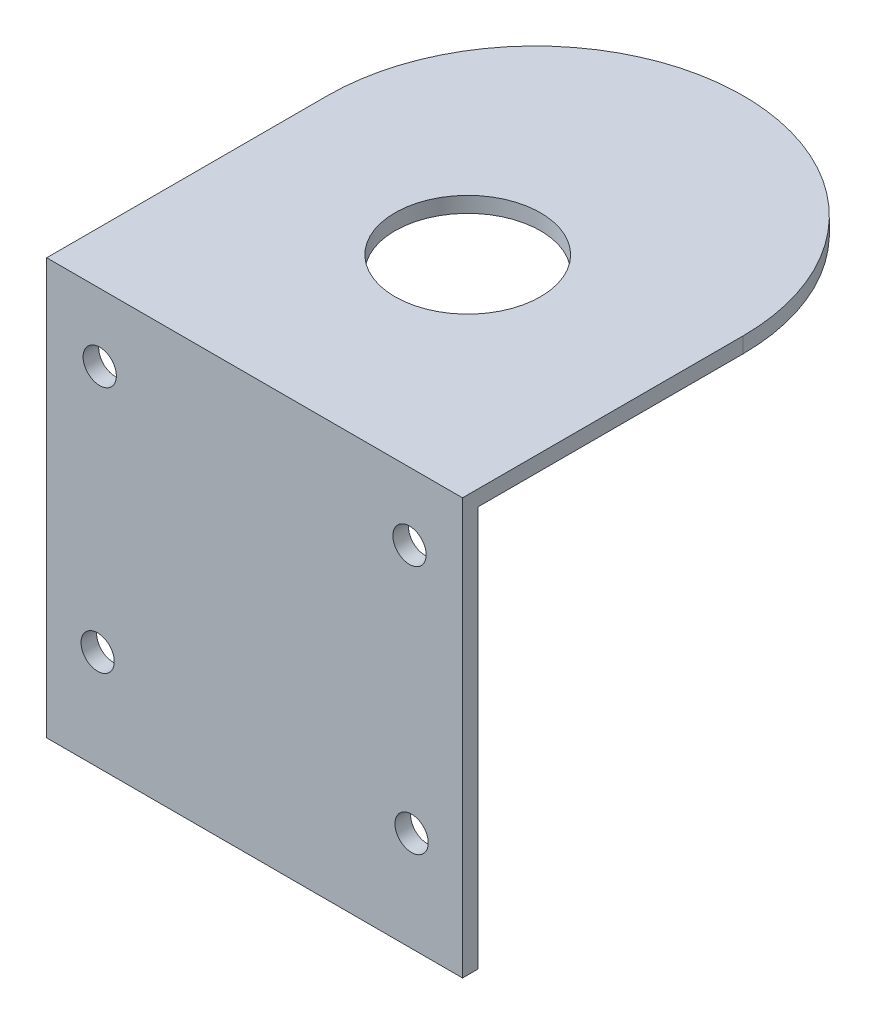
SolidWorks part; units mm, degrees
ref_plane "Front Plane" through (0, 0, 0) normal (0, 0, 1) x (1, 0, 0)
ref_plane "Top Plane" through (0, 0, 0) normal (0, 1, 0) x (1, 0, 0)
ref_plane "Right Plane" through (0, 0, 0) normal (1, 0, 0) x (0, 0, -1)
sketch "Sketch1" plane through (0, 0, 0) normal (0, 0, 1) x (1, 0, 0)
  line L0 (0, 0) -> (0, 9.1381) construction
  line L1 (-20, -20) -> (20, -20)
  line L2 (-20, -20) -> (-20, 20)
  line L3 (-20, 20) -> (20, 20)
  line L4 (20, -20) -> (20, 20)
  line L5 (-20, -20) -> (20, 20) construction
  line L6 (-20, 20) -> (20, -20) construction
  line L7 (0, 0) -> (8.2349, 0) construction
  circle A0 centre (14.9, 13.5) radius 1.6
  circle A1 centre (-14.9, 13.5) radius 1.6
  circle A4 centre (15.1, -10.3992) radius 1.6
  circle A5 centre (-15.1, -10.3992) radius 1.6
  point P0 (0, 0)
  dimension "D3" = 3.2
  dimension "D6" = 23.9
  dimension "D7" = 3.2
  dimension "D1" = 40
  dimension "D2" = 40
  dimension "D4" = 29.8
  dimension "D5" = 6.5
  dimension "D8" = 4.9
extrude "Boss-Extrude1" add sketch "Sketch1" along normal blind 1.5
sketch "Sketch3" plane through (0, 0, 0) normal (0, 0, -1) x (-1, 0, 0)
  line L0 (-20, -20) -> (-20, 20) construction
  line L1 (20, 20) -> (-20, 20)
  line L2 (20, 20) -> (20, 18.5)
  line L3 (20, 18.5) -> (-20, 18.5)
  line L4 (-20, 20) -> (-20, 18.5)
  dimension "D1" = 1.5
extrude "Boss-Extrude2" add sketch "Sketch3" along normal blind 45.5
sketch "Sketch4" plane through (0, 20, 0) normal (0, 1, 0) x (1, 0, 0)
  line L0 (-20, 45.5) -> (20, 45.5) construction
  line L1 (20, -1.5) -> (20, 45.5) construction
  line L3 (20, -1.5) -> (-20, -1.5)
  line L4 (20, -1.5) -> (20, 45.5)
  line L5 (20, 45.5) -> (-20, 45.5)
  line L6 (-20, -1.5) -> (-20, 45.5)
  circle A0 centre (0, 25.5) radius 20
  line M7 (20, 45.5) -> (-20, 45.5)
  line M8 (-20, 45.5) -> (-20, -1.5)
  dimension "D1" = 40
  dimension "D2" = 20
  dimension "D3" = 20
extrude "Cut-Extrude1" cut sketch "Sketch4" against normal through all contours A0 L4 M7 | A0 L5 M8
sketch "Sketch5" plane through (0, 20, 0) normal (0, 1, 0) x (1, 0, 0)
  line L0 (20, -1.5) -> (-20, -1.5) construction
  circle A0 centre (0, 19) radius 7
  dimension "D2" = 14
  dimension "D1" = 20.5
extrude "Cut-Extrude2" cut sketch "Sketch5" against normal through all
